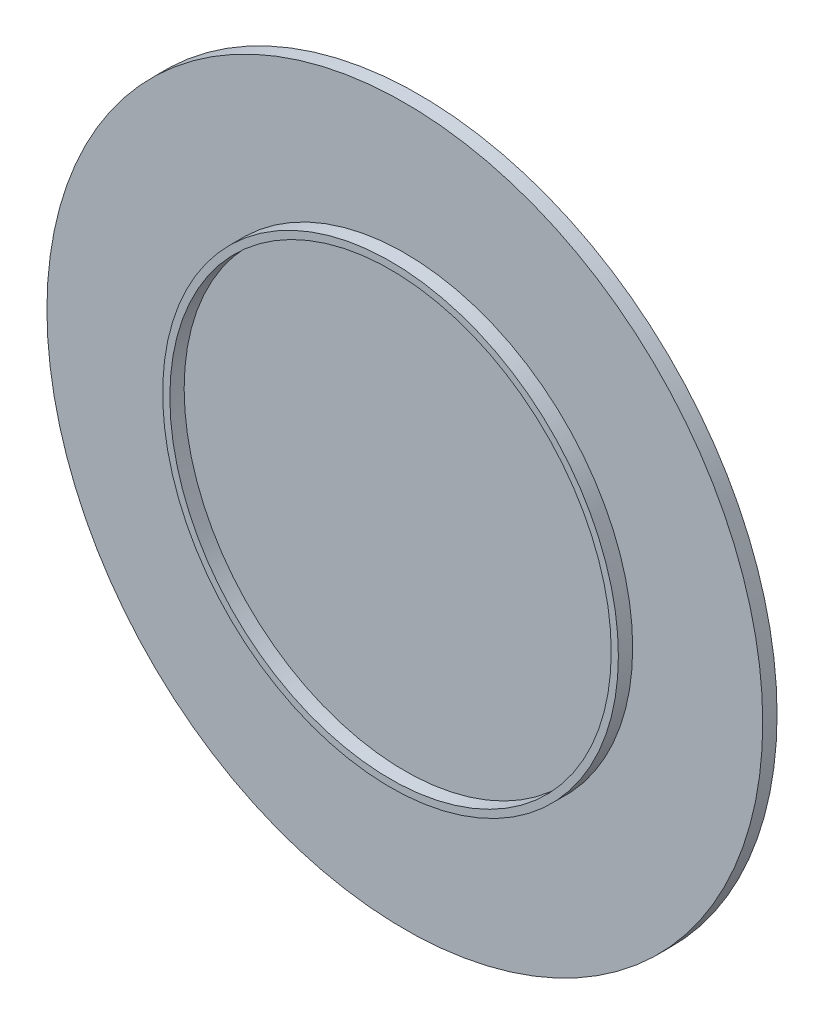
SolidWorks part; units mm, degrees
material "Chêne"
ref_plane "Plan de face" through (0, 0, 0) normal (0, 0, 1) x (1, 0, 0)
ref_plane "Plan de dessus" through (0, 0, 0) normal (0, 1, 0) x (1, 0, 0)
ref_plane "Plan de droite" through (0, 0, 0) normal (1, 0, 0) x (0, 0, -1)
sketch "Esquisse2" plane through (0, 0, 0) normal (0, 0, 1) x (1, 0, 0)
  circle A0 centre (0, 0) radius 159.1549
  dimension "D1" = 318.3099
extrude "Extru.-Mince1" add sketch "Esquisse2" along normal blind 10 thin thin type one direction reverse wall 5
sketch "Esquisse3" plane through (0, 0, 0) normal (0, 0, 1) x (1, 0, 0)
  circle A0 centre (0, 0) radius 250
  dimension "D1" = 500
extrude "Boss.-Extru.1" add sketch "Esquisse3" against normal blind 10
sketch "Esquisse5" plane through (0, 0, 0) normal (0, 0, 1) x (1, 0, 0)
  line L0 (0, 0) -> (0, 250) construction
  circle A0 centre (0, 0) radius 250 construction
ref_point "Point1"
ref_plane "Plan1" through (0, 159.1549, 0) normal (0, 1, 0) x (1, 0, 0)
